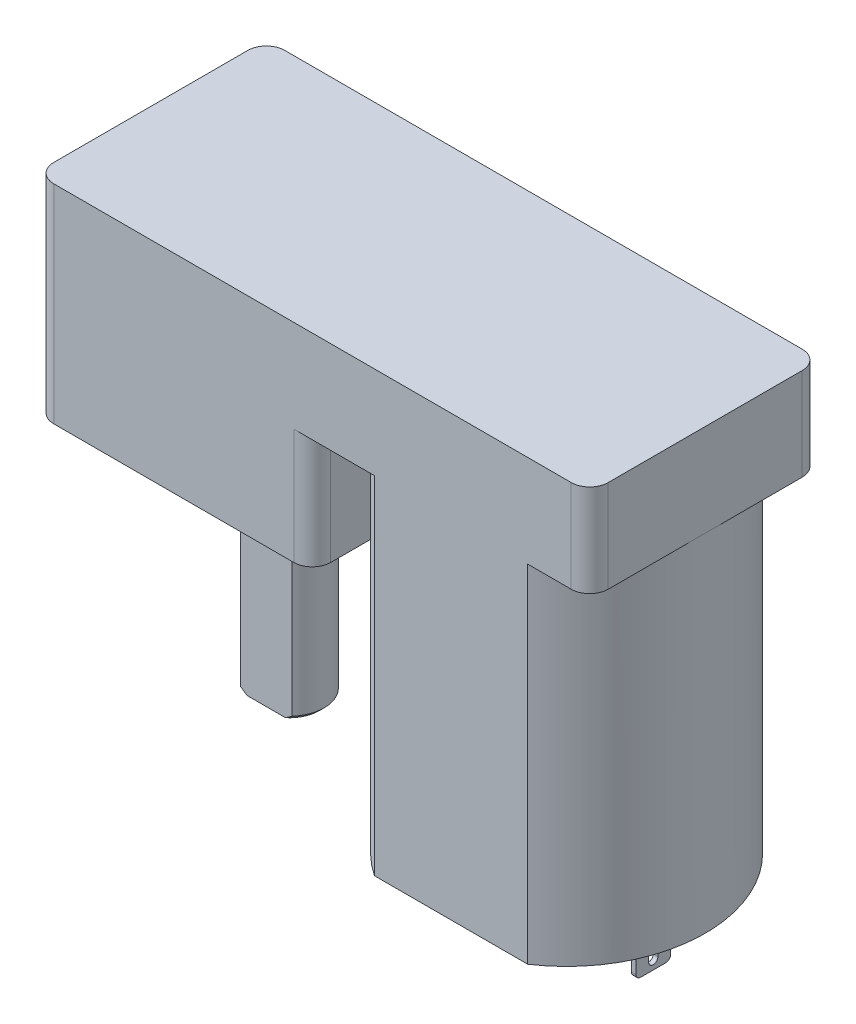
SolidWorks part; units mm, degrees
ref_plane "前视基准面" through (0, 0, 0) normal (0, 0, 1) x (1, 0, 0)
ref_plane "上视基准面" through (0, 0, 0) normal (0, 1, 0) x (1, 0, 0)
ref_plane "右视基准面" through (0, 0, 0) normal (1, 0, 0) x (0, 0, -1)
other "Configuration Table"
sketch "草图1" plane through (0, 0, 0) normal (0, 1, 0) x (1, 0, 0)
  line L0 (0, 0) -> (6, 0) construction
  line L1 (-3.3166, 5) -> (3.3166, 5)
  line L2 (-3.3166, -5) -> (3.3166, -5)
  circle A0 centre (0, 0) radius 6
  dimension "D1" = 12
  dimension "D2" = 5
extrude "凸台-拉伸1" add sketch "草图1" along normal blind 15
sketch "草图2" plane through (0, 0, 0) normal (0, -1, 0) x (1, 0, 0)
  circle A0 centre (0, 0) radius 2
  dimension "D1" = 4
extrude "凸台-拉伸2" add sketch "草图2" along normal blind 1
sketch "草图4" plane through (0, 15, 0) normal (0, 1, 0) x (1, 0, 0)
  line L0 (6, 0) -> (-18, 0) construction
  line L1 (-18, -5) -> (-18, 5)
  line L2 (-18, 5) -> (6, 5)
  line L3 (6, 5) -> (6, -5)
  line L4 (-18, -5) -> (6, -5)
  arc A0 (3.3166, -5) -> (3.3166, 5) centre (0, 0) ccw construction
  dimension "D1" = 24
  dimension "D2" = 5
  dimension "D3" = 5
extrude "凸台-拉伸3" add sketch "草图4" along normal blind 4
sketch "草图5" plane through (0, 15, 0) normal (0, -1, 0) x (1, 0, 0)
  line L0 (-3.3166, -5) -> (-18, -5) construction
  line L1 (-18, 5) -> (-6.01, 5)
  line L2 (-18, 5) -> (-18, -5)
  line L3 (-18, -5) -> (-6.01, -5)
  line L4 (-6.01, 5) -> (-6.01, -5)
  dimension "D1" = 11.99
extrude "凸台-拉伸6" add sketch "草图5" along normal blind 5
sketch "草图6" plane through (0, 10, 0) normal (0, -1, 0) x (1, 0, 0)
  line L0 (-18, 0) -> (-6, 0) construction
  line L1 (-18, 5) -> (-18, -5) construction
  line L2 (-13.118, 1) -> (-10.882, 1)
  arc A0 (-3.3166, 5) -> (-3.3166, -5) centre (0, 0) ccw construction
  circle A1 centre (-12, 0) radius 1.5
  dimension "D1" = 3
  dimension "D2" = 1
extrude "凸台-拉伸7" add sketch "草图6" along normal blind 10 contours A1 L0 L2 | L0 A1
sketch "草图7" plane through (0, 10, 0) normal (0, -1, 0) x (1, 0, 0)
  circle A0 centre (-12, 0) radius 2
  dimension "D1" = 4
extrude "凸台-拉伸8" add sketch "草图7" along normal blind 1
sketch "草图8" plane through (0, 0, 0) normal (0, -1, 0) x (1, 0, 0)
  line L0 (0, 0) -> (-3.65, 0) construction
  line L1 (0, 0) -> (0, -2) construction
  line L2 (-3.75, -0.75) -> (-3.55, -0.75)
  line L3 (-3.75, -0.75) -> (-3.75, 0.75)
  line L4 (-3.75, 0.75) -> (-3.55, 0.75)
  line L5 (-3.55, -0.75) -> (-3.55, 0.75)
  line L6 (-3.75, -0.75) -> (-3.55, 0.75) construction
  line L7 (-3.75, 0.75) -> (-3.55, -0.75) construction
  line L8 (3.75, 0.75) -> (3.55, -0.75) construction
  line L9 (3.75, -0.75) -> (3.55, 0.75) construction
  line L10 (3.55, -0.75) -> (3.55, 0.75)
  line L11 (3.75, 0.75) -> (3.55, 0.75)
  line L12 (3.75, -0.75) -> (3.75, 0.75)
  line L13 (3.75, -0.75) -> (3.55, -0.75)
  circle A0 centre (0, 0) radius 2 construction
  dimension "D1" = 3.65
  dimension "D2" = 0.2
  dimension "D3" = 1.5
extrude "凸台-拉伸9" add sketch "草图8" along normal blind 2.5
sketch "草图9" plane through (3.75, 0, 0) normal (1, 0, 0) x (0, 0, -1)
  line L0 (0, 0) -> (0, -2.5) construction
  line L1 (0.75, 0) -> (-0.75, 0) construction
  line L2 (0.75, -2.5) -> (-0.75, -2.5) construction
  line L3 (0, -2.1) -> (0, -1.6) construction
  line L4 (-0.2, -2.1) -> (-0.2, -1.6)
  line L5 (0.2, -2.1) -> (0.2, -1.6)
  arc A0 (-0.2, -2.1) -> (0.2, -2.1) centre (0, -2.1) ccw
  arc A1 (0.2, -1.6) -> (-0.2, -1.6) centre (0, -1.6) ccw
  point P8 (0, -1.85)
  dimension "D1" = 0.4
  dimension "D2" = 0.4
  dimension "D3" = 0.5
extrude "切除-拉伸1" cut sketch "草图9" against normal blind 9.5
fillet "圆角1" radius 0.2 4 edges at (-3.65, -2.5, -0.75) (-3.65, -2.5, 0.75) (3.65, -2.5, -0.75) (3.65, -2.5, 0.75)
fillet "圆角2" radius 0.2 1 edges at (0, -1, -2)
fillet "圆角3" radius 0.8 6 edges at (6, 17, -5) (6, 17, 5) (-18, 14.5, -5) (-18, 14.5, 5) (-6.01, 12.5, -5) (-6.01, 12.5, 5)
chamfer "倒角1" distance 0.2 angle 45 1 edges at (-12, 0, -1.5)
